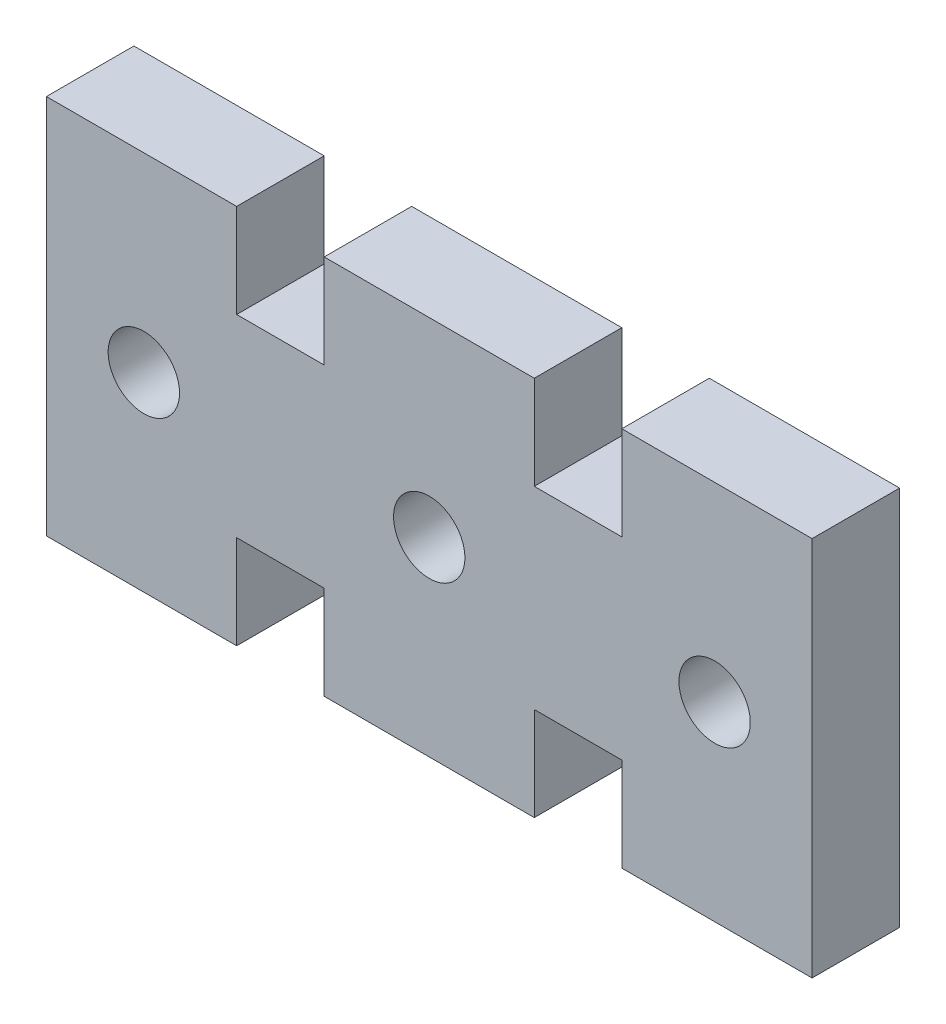
SolidWorks part; units mm, degrees
ref_plane "Front Plane" through (0, 0, 0) normal (0, 0, 1) x (1, 0, 0)
ref_plane "Top Plane" through (0, 0, 0) normal (0, 1, 0) x (1, 0, 0)
ref_plane "Right Plane" through (0, 0, 0) normal (1, 0, 0) x (0, 0, -1)
sketch "Sketch1" plane through (0, 0, 0) normal (0, 0, 1) x (1, 0, 0)
  line L0 (0, 12.7) -> (0, -12.7) construction
  line L1 (25.554, -12.7) -> (12.854, -12.7)
  line L2 (25.554, -12.7) -> (25.554, 12.7)
  line L3 (25.554, 12.7) -> (12.854, 12.7)
  line L4 (-25.554, -12.7) -> (-25.554, 12.7)
  line L5 (25.554, -12.7) -> (-25.554, 12.7) construction
  line L6 (25.554, 12.7) -> (-25.554, -12.7) construction
  line L7 (-7.012, 6.45) -> (-12.854, 6.45)
  line L8 (-7.012, 6.45) -> (-7.012, 12.7)
  line L9 (-7.012, -6.45) -> (-7.012, -12.7)
  line L10 (-12.854, 6.45) -> (-12.854, 12.7)
  line L11 (-7.012, 6.45) -> (-12.854, 12.7) construction
  line L12 (-7.012, 12.7) -> (-12.854, 6.45) construction
  line L13 (25.554, 0) -> (-25.554, 0) construction
  line L14 (-12.854, 12.7) -> (-25.554, 12.7)
  line L15 (-7.012, -6.45) -> (-12.854, -6.45)
  line L16 (-7.012, -12.7) -> (-12.854, -6.45) construction
  line L17 (-7.012, -6.45) -> (-12.854, -12.7) construction
  line L18 (-12.854, -6.45) -> (-12.854, -12.7)
  line L19 (7.012, -6.45) -> (12.854, -12.7) construction
  line L20 (7.012, -12.7) -> (12.854, -6.45) construction
  line L21 (12.854, -6.45) -> (12.854, -12.7)
  line L22 (7.012, -6.45) -> (12.854, -6.45)
  line L23 (7.012, -6.45) -> (7.012, -12.7)
  line L24 (7.012, 12.7) -> (12.854, 6.45) construction
  line L25 (7.012, 6.45) -> (12.854, 12.7) construction
  line L26 (12.854, 6.45) -> (12.854, 12.7)
  line L27 (7.012, 6.45) -> (7.012, 12.7)
  line L28 (7.012, 6.45) -> (12.854, 6.45)
  line L29 (-12.854, -12.7) -> (-25.554, -12.7)
  line L30 (7.012, -12.7) -> (-7.012, -12.7)
  line L31 (7.012, 12.7) -> (-7.012, 12.7)
  circle A0 centre (0, 0) radius 2.3813
  circle A1 centre (-19.05, 0) radius 2.3812
  circle A2 centre (19.05, 0) radius 2.3812
  point P0 (0, 0)
  point P6 (-9.933, 9.575)
  point P31 (9.933, 9.575)
  dimension "D6" = 4.7625
  dimension "D7" = 2
  dimension "D1" = 51.108
  dimension "D2" = 25.4
  dimension "D3" = 6.25
  dimension "D4" = 5.842
  dimension "D5" = 12.854
extrude "Boss-Extrude1" add sketch "Sketch1" along normal blind 5.842
